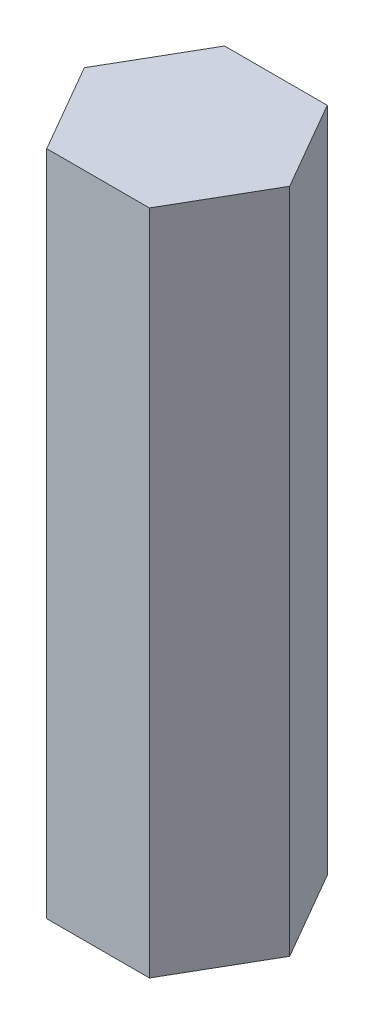
SolidWorks part; units mm, degrees
ref_plane "Front Plane" through (0, 0, 0) normal (0, 0, 1) x (1, 0, 0)
ref_plane "Top Plane" through (0, 0, 0) normal (0, 1, 0) x (1, 0, 0)
ref_plane "Right Plane" through (0, 0, 0) normal (1, 0, 0) x (0, 0, -1)
sketch "Sketch1" plane through (0, 0, 0) normal (0, 1, 0) x (1, 0, 0)
  line L1 (4.6188, 0) -> (2.3094, 4)
  line L2 (2.3094, 4) -> (-2.3094, 4)
  line L3 (-2.3094, 4) -> (-4.6188, 0)
  line L4 (-4.6188, 0) -> (-2.3094, -4)
  line L5 (-2.3094, -4) -> (2.3094, -4)
  line L6 (2.3094, -4) -> (4.6188, 0)
  circle A0 centre (0, 0) radius 4 construction
  dimension "D1" = 8
extrude "Boss-Extrude1" add sketch "Sketch1" along normal blind 30
